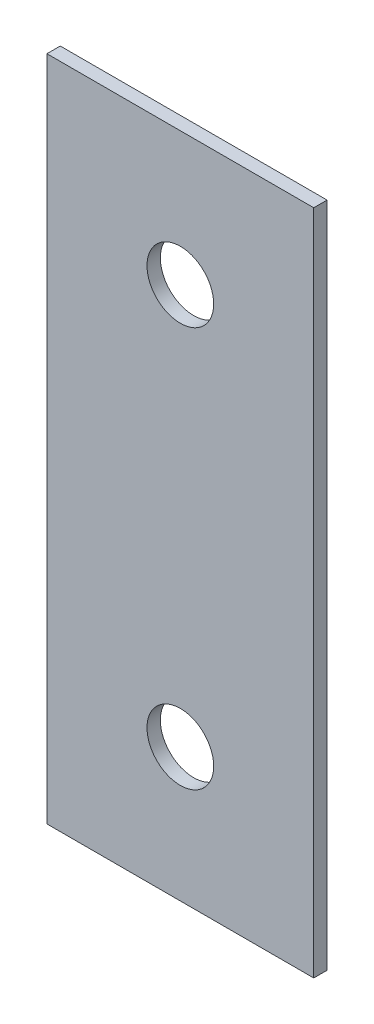
SolidWorks part; units mm, degrees
ref_plane "Alzado" through (0, 0, 0) normal (0, 0, 1) x (1, 0, 0)
ref_plane "Planta" through (0, 0, 0) normal (0, 1, 0) x (1, 0, 0)
ref_plane "Vista lateral" through (0, 0, 0) normal (1, 0, 0) x (0, 0, -1)
sketch "Croquis1" plane through (0, 0, 0) normal (0, 0, 1) x (1, 0, 0)
  line L0 (0, 0) -> (0, 15) construction
  line L1 (10, -25) -> (-10, -25)
  line L2 (10, -25) -> (10, 25)
  line L3 (10, 25) -> (-10, 25)
  line L4 (-10, -25) -> (-10, 25)
  line L5 (10, -25) -> (-10, 25) construction
  line L6 (10, 25) -> (-10, -25) construction
  line L7 (0, 0) -> (0, -15) construction
  circle A0 centre (0, 15) radius 2.5
  circle A1 centre (0, -15) radius 2.5
  point P0 (0, 0)
  dimension "D5" = 5
  dimension "D6" = 5
  dimension "D1" = 50
  dimension "D2" = 20
  dimension "D3" = 15
  dimension "D4" = 15
extrude "Saliente-Extruir1" add sketch "Croquis1" along normal blind 1
